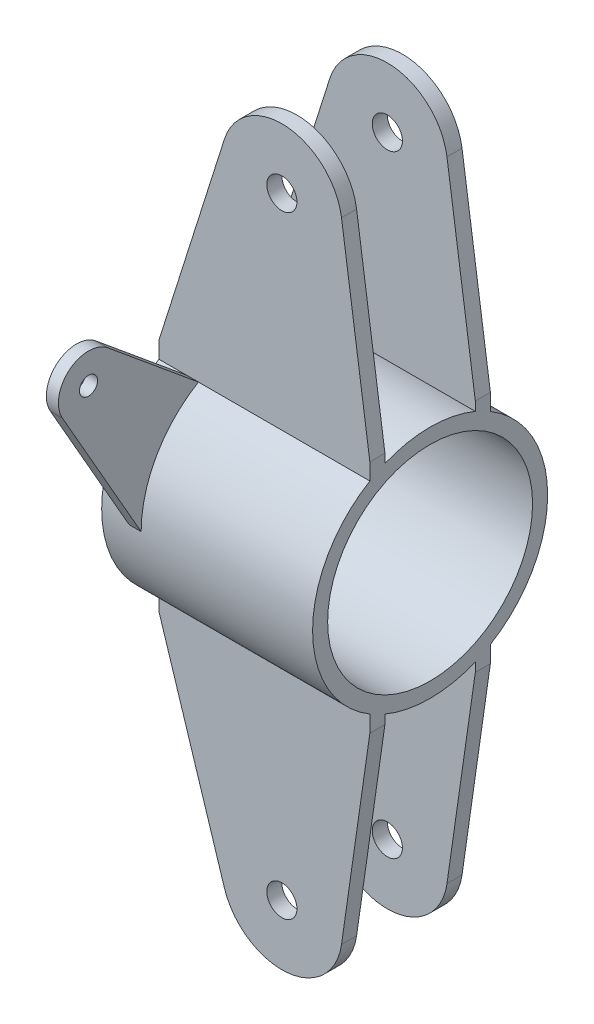
SolidWorks part; units mm, degrees
ref_plane "Front Plane" through (0, 0, 0) normal (0, 0, 1) x (1, 0, 0)
ref_plane "Top Plane" through (0, 0, 0) normal (0, 1, 0) x (1, 0, 0)
ref_plane "Right Plane" through (0, 0, 0) normal (1, 0, 0) x (0, 0, -1)
sketch "Sketch1" plane through (0, 0, 0) normal (1, 0, 0) x (0, 0, -1)
  circle A0 centre (0, 0) radius 34.007
  circle A1 centre (0, 0) radius 39.007
  dimension "D1" = 68.014
  dimension "D2" = 78.014
extrude "Boss-Extrude1" add sketch "Sketch1" along normal mid plane 70
sketch "Sketch2" plane through (0, 0, 0) normal (0, 0, 1) x (1, 0, 0)
  line L0 (-35, 0) -> (5.8, 0) construction
  line L1 (-35, 39.007) -> (-35, -39.007) construction
  line L2 (5.8, 101.6) -> (5.8, -101.6) construction
  line L3 (-35, -39.007) -> (35, -39.007) construction
  line L4 (35, 39.007) -> (-35, 39.007) construction
  line L5 (-35, -39.007) -> (35, -39.007)
  line L6 (35, 39.007) -> (-35, 39.007)
  line L7 (-35, 39.007) -> (-13.2668, 107.6378)
  line L8 (35, 39.007) -> (25.5966, 104.4448)
  line L9 (-35, -39.007) -> (-13.2668, -107.6378)
  line L10 (35, -39.007) -> (25.5966, -104.4448)
  circle A0 centre (5.8, 101.6) radius 5.007
  circle A1 centre (5.8, -101.6) radius 5.007
  arc A2 (25.5966, 104.4448) -> (-13.2668, 107.6378) centre (5.8, 101.6) ccw
  arc A3 (-13.2668, -107.6378) -> (25.5966, -104.4448) centre (5.8, -101.6) ccw
  point P8 (5.8, 0)
  dimension "D3" = 10.014
  dimension "D4" = 40
  dimension "D1" = 40.8
  dimension "D2" = 203.2
extrude "Boss-Extrude2" add sketch "Sketch2" along normal blind 5 from offset 15 separate body
sketch "Sketch3" plane through (0, 0, 0) normal (0, 0, 1) x (1, 0, 0)
  line L0 (-35, -39.007) -> (-13.2668, -107.6378) construction
  line L1 (25.5966, -104.4448) -> (35, -39.007) construction
  line L2 (35, -39.007) -> (-35, -39.007) construction
  line L3 (-35, 39.007) -> (35, 39.007) construction
  line L4 (-13.2668, 107.6378) -> (-35, 39.007) construction
  line L5 (35, 39.007) -> (25.5966, 104.4448) construction
  line L6 (-35, -39.007) -> (-13.2668, -107.6378)
  line L7 (25.5966, -104.4448) -> (35, -39.007)
  line L8 (35, -39.007) -> (-35, -39.007)
  line L9 (-35, 39.007) -> (35, 39.007)
  line L10 (-13.2668, 107.6378) -> (-35, 39.007)
  line L11 (35, 39.007) -> (25.5966, 104.4448)
  circle A0 centre (5.8, -101.6) radius 5.007 construction
  arc A1 (-13.2668, -107.6378) -> (25.5966, -104.4448) centre (5.8, -101.6) ccw construction
  circle A2 centre (5.8, 101.6) radius 5.007 construction
  arc A3 (25.5966, 104.4448) -> (-13.2668, 107.6378) centre (5.8, 101.6) ccw construction
  circle A4 centre (5.8, -101.6) radius 5.007
  arc A5 (-13.2668, -107.6378) -> (25.5966, -104.4448) centre (5.8, -101.6) ccw
  circle A6 centre (5.8, 101.6) radius 5.007
  arc A7 (25.5966, 104.4448) -> (-13.2668, 107.6378) centre (5.8, 101.6) ccw
extrude "Boss-Extrude3" add sketch "Sketch3" against normal blind 5 from offset 15 separate body offset against normal yes
sketch "Sketch4" plane through (35, 0, 0) normal (1, 0, 0) x (0, 0, -1)
  line L0 (20, -39.007) -> (15, -39.007) construction
  line L1 (-20, -39.007) -> (-15, -39.007) construction
  line L2 (-20, 39.007) -> (-15, 39.007) construction
  line L3 (20, 39.007) -> (15, 39.007) construction
  line L4 (20, -39.007) -> (15, -39.007)
  line L5 (-20, -39.007) -> (-15, -39.007)
  line L6 (-20, 39.007) -> (-15, 39.007)
  line L7 (20, 39.007) -> (15, 39.007)
  line L8 (-20, 39.007) -> (-20, 33.4895)
  line L9 (-15, 39.007) -> (-15, 36.0076)
  line L10 (15, 39.007) -> (15, 36.0076)
  line L11 (20, 39.007) -> (20, 33.4895)
  line L12 (-20, -39.007) -> (-20, -33.4895)
  line L13 (-15, -39.007) -> (-15, -36.0076)
  line L14 (15, -39.007) -> (15, -36.0076)
  line L15 (20, -39.007) -> (20, -33.4895)
  circle A0 centre (0, 0) radius 39.007 construction
  arc A1 (-20, -33.4895) -> (-15, -36.0076) centre (0, 0) ccw
  arc A2 (20, 33.4895) -> (15, 36.0076) centre (0, 0) ccw
  arc A3 (-15, 36.0076) -> (-20, 33.4895) centre (0, 0) ccw
  arc A4 (15, -36.0076) -> (20, -33.4895) centre (0, 0) ccw
extrude "Boss-Extrude4" add sketch "Sketch4" against normal up to surface (70 mm away) up to face at (-35, 0, -39.007)
ref_plane "Plane1" through (-25.9, 0, 0) normal (-1, 0, 0) x (0, 0, 1)
sketch "Sketch5" plane through (-25.9, 0, 0) normal (-1, 0, 0) x (0, 0, 1)
  line L0 (0, 0) -> (39.007, 0) construction
  line L1 (0, 0) -> (0, 99.7912) construction
  line L2 (0, 0) -> (56.4709, 50.6685) construction
  line L3 (50.0988, 58.3754) -> (20, 33.4895)
  line L4 (39.007, 0) -> (65.1511, 45.7031)
  arc A0 (20, -33.4895) -> (20, 33.4895) centre (0, 0) ccw construction
  arc A1 (39.007, 0) -> (20, 33.4895) centre (0, 0) ccw
  circle A2 centre (0, 0) radius 75.87 construction
  circle A3 centre (56.4709, 50.6685) radius 3
  arc A4 (65.1511, 45.7031) -> (50.0988, 58.3754) centre (56.4709, 50.6685) ccw
  dimension "D1" = 151.74
  dimension "D3" = 6
  dimension "D4" = 20
  dimension "D2" = 48.1
extrude "Boss-Extrude5" add sketch "Sketch5" against normal blind 4
